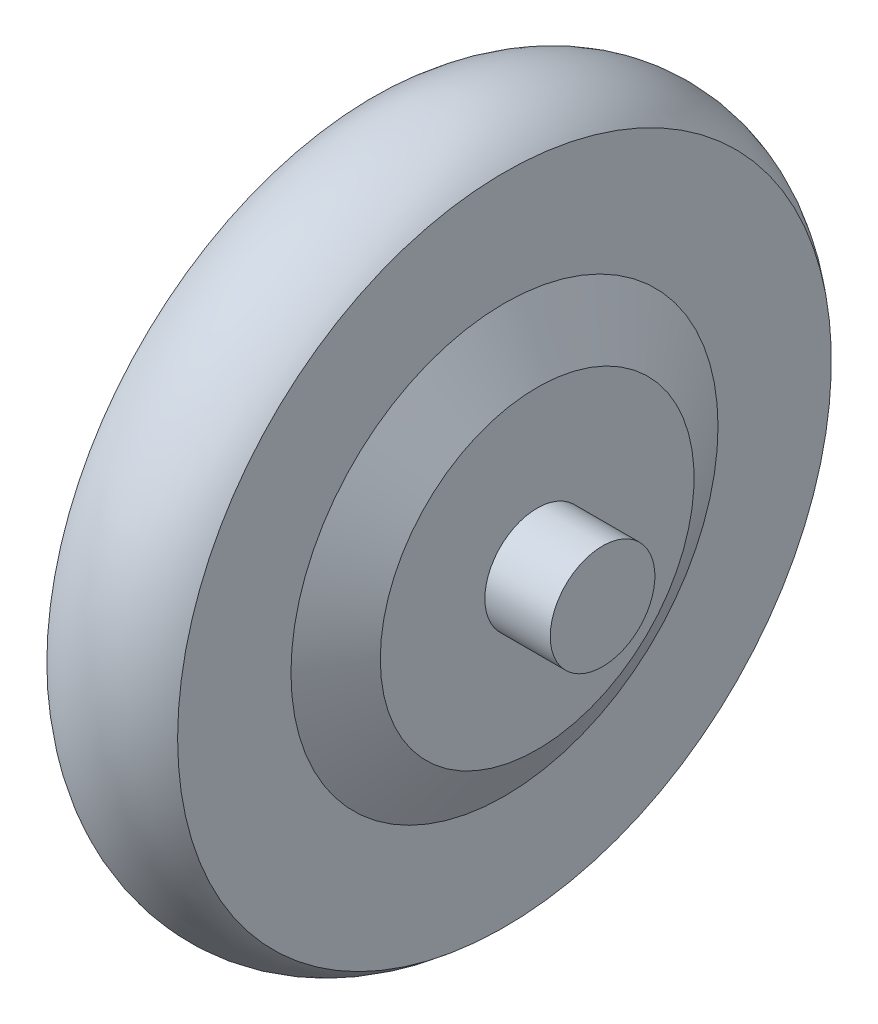
SolidWorks part; units mm, degrees
ref_plane "前视基准面" through (0, 0, 0) normal (0, 0, 1) x (1, 0, 0)
ref_plane "上视基准面" through (0, 0, 0) normal (0, 1, 0) x (1, 0, 0)
ref_plane "右视基准面" through (0, 0, 0) normal (1, 0, 0) x (0, 0, -1)
sketch "草图1" plane through (0, 0, 0) normal (0, 0, 1) x (1, 0, 0)
  line L0 (20, 0) -> (25, 0)
  line L1 (0, 0) -> (20, 0)
  line L2 (0, 32.6603) -> (0, 50)
  line L4 (20, 32.6603) -> (20, 50)
  line L5 (25, 0) -> (25, 24)
  line L6 (25, 24) -> (20, 32.6603)
  line L7 (10, 38.8197) -> (10, 0) construction
  line L8 (-5, 24) -> (0, 32.6603)
  line L9 (-5, 12) -> (-5, 24)
  line L10 (0, 0) -> (-5, 0)
  line L11 (-5, 0) -> (-13, 0)
  line L12 (-13, 0) -> (-13, 12)
  line L13 (-13, 12) -> (-5, 12)
  arc A0 (20, 50) -> (0, 50) centre (10, 38.8197) ccw
revolve "旋转1" add sketch "草图1" angle 360 about L1
sketch "草图2" plane through (-13, 0, 0) normal (-1, 0, 0) x (0, 0, 1)
  circle A0 centre (0, 0) radius 8
extrude "凸台-拉伸1" add sketch "草图2" along normal blind 10 and the other way blind 48
sketch "草图3" plane through (0, 0, 0) normal (0, 1, 0) x (1, 0, 0)
  line L3 (-6.8, -4) -> (-11.2, -4)
  line L6 (-11.2, 4) -> (-6.8, 4)
  line L9 (-6.8, 4) -> (-6.8, -4)
  line L11 (-11.2, 4) -> (-11.2, -4)
extrude "凸台-拉伸2" add sketch "草图3" along normal blind 14
